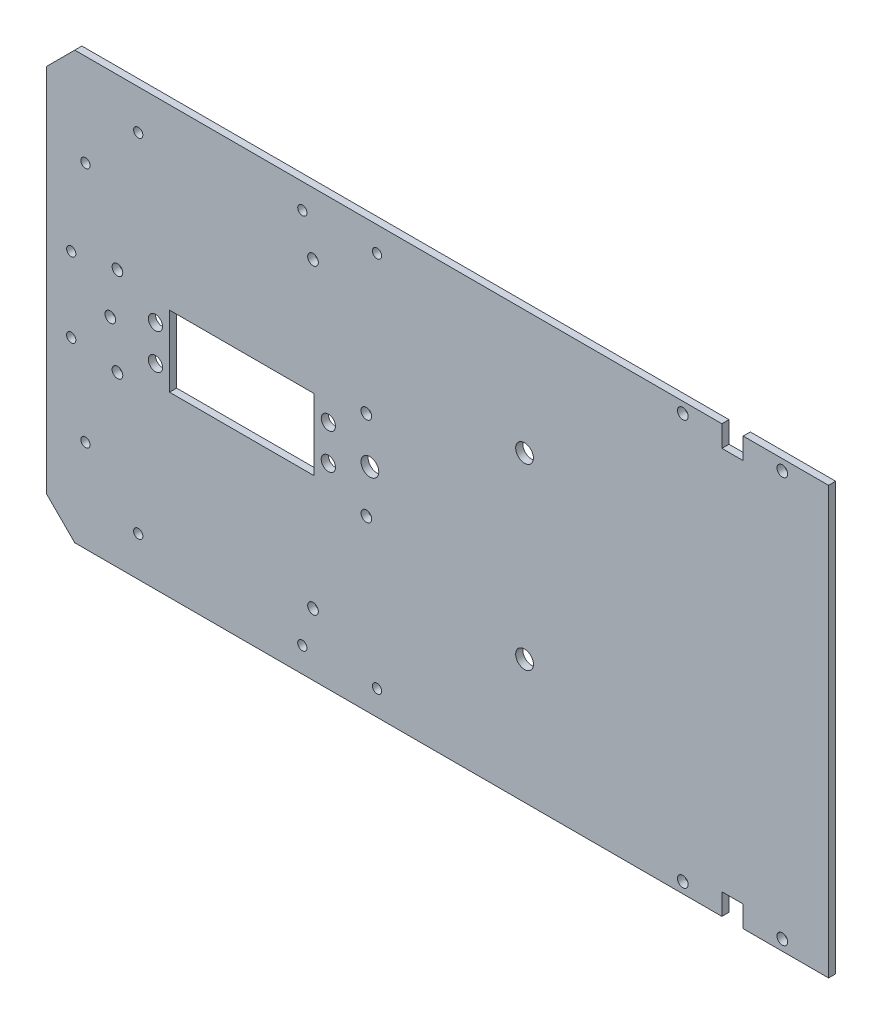
SolidWorks part; units mm, degrees
ref_plane "前视基准面" through (0, 0, 0) normal (0, 0, 1) x (1, 0, 0)
ref_plane "上视基准面" through (0, 0, 0) normal (0, 1, 0) x (1, 0, 0)
ref_plane "右视基准面" through (0, 0, 0) normal (1, 0, 0) x (0, 0, -1)
sketch "草图5" plane through (0, 0, 0) normal (0, 0, 1) x (1, 0, 0)
  line L1 (-110, 60) -> (110, 60)
  line L2 (-110, 60) -> (-110, -60)
  line L3 (-110, -60) -> (110, -60)
  line L4 (110, 60) -> (110, -60)
  line L5 (-110, 60) -> (110, -60) construction
  line L6 (-110, -60) -> (110, 60) construction
  point P0 (0, 0)
  dimension "D1" = 120
  dimension "D2" = 220
extrude "凸台-拉伸2" add sketch "草图5" along normal blind 2
sketch "草图6" plane through (0, 0, 2) normal (0, 0, 1) x (1, 0, 0)
  line L0 (-110, 60) -> (-110, -60) construction
  line L1 (110, -60) -> (110, 60) construction
  line L2 (110, 0) -> (-110, 0) construction
  circle A0 centre (-19, 0) radius 2.5
  circle A1 centre (24.5, 25.1147) radius 2.5
  circle A2 centre (24.5, -25.1147) radius 2.5
  point P15 (10, 0)
  dimension "D2" = 29
  dimension "D4" = 5
  dimension "D3" = 120
  dimension "D1" = 3
extrude "切除-拉伸3" cut sketch "草图6" against normal through all
sketch "草图7" plane through (0, 0, 2) normal (0, 0, 1) x (1, 0, 0)
  line L0 (-110, 0) -> (110, 0) construction
  line L1 (-110, 60) -> (-110, -60) construction
  line L2 (110, -60) -> (110, 60) construction
  line L3 (110, 60) -> (-110, 60) construction
  line L4 (80, 60) -> (86, 60)
  line L5 (80, 60) -> (80, 54)
  line L6 (80, 54) -> (86, 54)
  line L7 (86, 60) -> (86, 54)
  line L8 (83, 60) -> (83, 54) construction
  line L9 (52.9399, 57) -> (80, 57) construction
  line L10 (80, 57) -> (86, 57) construction
  line L11 (86, 57) -> (94.1573, 57) construction
  line L12 (80, -60) -> (80, -54)
  line L13 (80, -54) -> (86, -54)
  line L14 (86, -60) -> (86, -54)
  line L15 (80, -60) -> (86, -60)
  circle A0 centre (69, 57) radius 1.5
  circle A1 centre (97, 57) radius 1.5
  circle A2 centre (97, -57) radius 1.5
  circle A3 centre (69, -57) radius 1.5
  dimension "D4" = 28
  dimension "D5" = 3
  dimension "D1" = 6
  dimension "D2" = 6
  dimension "D3" = 190
extrude "切除-拉伸4" cut sketch "草图7" against normal through all
sketch "草图9" plane through (0, 0, 2) normal (0, 0, 1) x (1, 0, 0)
  line L0 (-110, 0) -> (110, 0) construction
  line L1 (-110, 60) -> (-110, -60) construction
  line L2 (110, -60) -> (110, 60) construction
  line L3 (-55, -10) -> (-55, 10) construction
  line L4 (-75.35, 10) -> (-34.65, 10)
  line L5 (-75.35, 10) -> (-75.35, -10)
  line L6 (-75.35, -10) -> (-34.65, -10)
  line L7 (-34.65, 10) -> (-34.65, -10)
  line L8 (-75.35, 10) -> (-34.65, -10) construction
  line L9 (-75.35, -10) -> (-34.65, 10) construction
  circle A0 centre (-79.315, 5) radius 2
  circle A1 centre (-79.315, -5) radius 2
  circle A2 centre (-30.685, -5) radius 2
  circle A3 centre (-30.685, 5) radius 2
  point P6 (-55, 0)
  dimension "D4" = 4
  dimension "D5" = 10
  dimension "D6" = 48.63
  dimension "D1" = 40.7
  dimension "D2" = 20
  dimension "D3" = 55
extrude "切除-拉伸6" cut sketch "草图9" against normal through all
sketch "草图13" plane through (0, 0, 2) normal (0, 0, 1) x (1, 0, 0)
  line L0 (-110, 0) -> (110, 0) construction
  line L1 (-110, 60) -> (-110, -60) construction
  line L2 (110, -60) -> (110, 60) construction
  circle A0 centre (-103, 10.5) radius 1.3
  circle A1 centre (-103, -10.5) radius 1.3
  dimension "D1" = 2.6
  dimension "D2" = 21
  dimension "D3" = 7
extrude "切除-拉伸10" cut sketch "草图13" against normal through all
chamfer "倒角1" distance 8 angle 45 2 edges at (-110, -60, 1) (-110, 60, 1)
sketch "草图15" plane through (0, 0, 2) normal (0, 0, 1) x (1, 0, 0)
  line L0 (-110, 0) -> (110, 0) construction
  line L1 (-110, 52) -> (-110, -52) construction
  line L2 (110, -60) -> (110, 60) construction
  line L3 (80, 60) -> (-102, 60) construction
  circle A0 centre (-38, 53) radius 1.3
  circle A1 centre (-38, -53) radius 1.3
  circle A2 centre (-17, 53) radius 1.3
  circle A3 centre (-17, -53) radius 1.3
  dimension "D1" = 7
  dimension "D2" = 2.6
  dimension "D3" = 72
  dimension "D4" = 21
extrude "切除-拉伸12" cut sketch "草图15" against normal through all
sketch "草图16" plane through (0, 0, 2) normal (0, 0, 1) x (1, 0, 0)
  line L0 (-110, 0) -> (110, 0) construction
  line L1 (-110, 52) -> (-110, -52) construction
  line L2 (110, -60) -> (110, 60) construction
  line L3 (80, 60) -> (-102, 60) construction
  line L4 (-99, 34) -> (-67.4664, 65.5336) construction
  circle A0 centre (-99, 34) radius 1.3
  circle A1 centre (-84.1508, 48.8492) radius 1.3
  circle A2 centre (-99, -34) radius 1.3
  circle A3 centre (-84.1508, -48.8492) radius 1.3
  dimension "D1" = 11
  dimension "D2" = 26
  dimension "D3" = 21
extrude "切除-拉伸13" cut sketch "草图16" against normal through all
sketch "草图17" plane through (0, 0, 2) normal (0, 0, 1) x (1, 0, 0)
  line L0 (-110, 0) -> (110, 0) construction
  line L1 (-110, 52) -> (-110, -52) construction
  line L2 (110, -60) -> (110, 60) construction
  circle A2 centre (-20, 12.5) radius 1.5
  circle A3 centre (-20, -12.5) radius 1.5
  circle A4 centre (-90, 12.5) radius 1.5
  circle A5 centre (-90, -12.5) radius 1.5
  dimension "D1" = 3
  dimension "D2" = 3
  dimension "D3" = 25
  dimension "D4" = 90
  dimension "D5" = 20
  dimension "D6" = 25
  dimension "D7" = 3
extrude "切除-拉伸14" cut sketch "草图17" against normal through all
sketch "草图19" plane through (0, 0, 2) normal (0, 0, 1) x (1, 0, 0)
  line L0 (-110, 0) -> (110, 0) construction
  line L1 (-110, 52) -> (-110, -52) construction
  line L2 (110, -60) -> (110, 60) construction
  circle A0 centre (-92, 0) radius 1.5
  circle A1 centre (-35, 42.5) radius 1.5
  circle A2 centre (-35, -42.5) radius 1.5
  dimension "D1" = 3
  dimension "D2" = 18
  dimension "D3" = 85
  dimension "D4" = 75
extrude "切除-拉伸15" cut sketch "草图19" against normal through all
